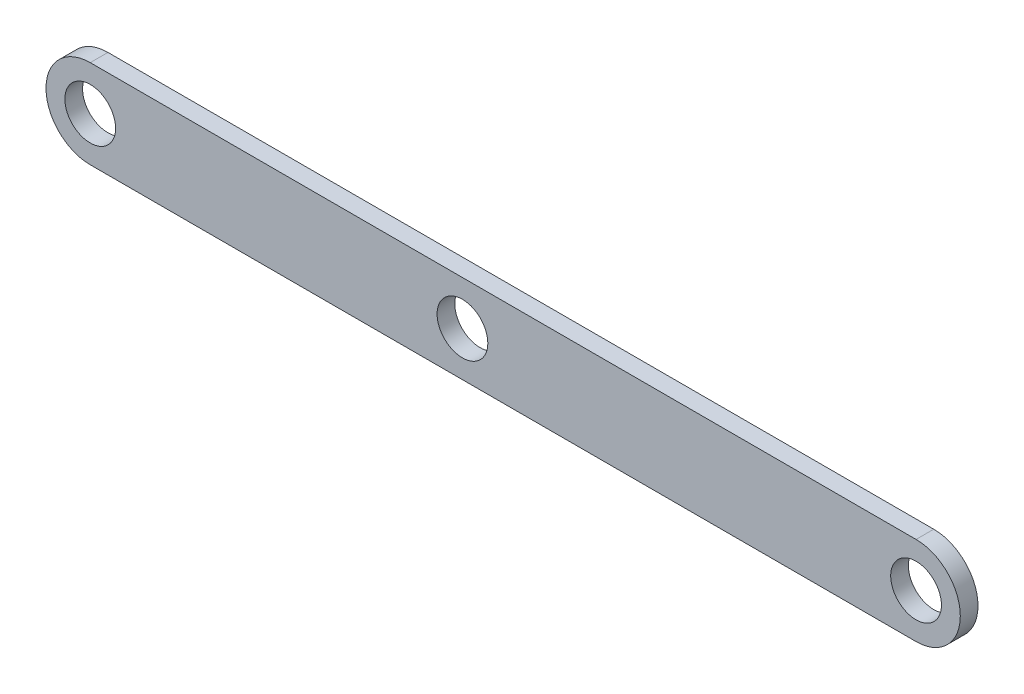
SolidWorks part; units mm, degrees
material "PBT General Purpose"
ref_plane "Front Plane" through (0, 0, 0) normal (0, 0, 1) x (1, 0, 0)
ref_plane "Top Plane" through (0, 0, 0) normal (0, 1, 0) x (1, 0, 0)
ref_plane "Right Plane" through (0, 0, 0) normal (1, 0, 0) x (0, 0, -1)
sketch "Sketch1" plane through (0, 0, 0) normal (0, 0, 1) x (1, 0, 0)
  line L0 (0, 7.5) -> (140, 7.5)
  line L6 (0, -7.5) -> (140, -7.5)
  arc A2 (0, 7.5) -> (0, -7.5) centre (0, 0) ccw
  arc A3 (140, -7.5) -> (140, 7.5) centre (140, 0) ccw
  dimension "D1" = 15
  dimension "D2" = 140
extrude "Boss-Extrude1" add sketch "Sketch1" along normal blind 3
sketch "Sketch2" plane through (0, 0, 3) normal (0, 0, 1) x (1, 0, 0)
  circle A0 centre (0, 0) radius 4.3
  circle A2 centre (140, 0) radius 4.3
  circle A3 centre (63.1, 0) radius 4.3
  dimension "D1" = 8.6
  dimension "D2" = 140
  dimension "D3" = 76.9
extrude "Cut-Extrude1" cut sketch "Sketch2" against normal through all
